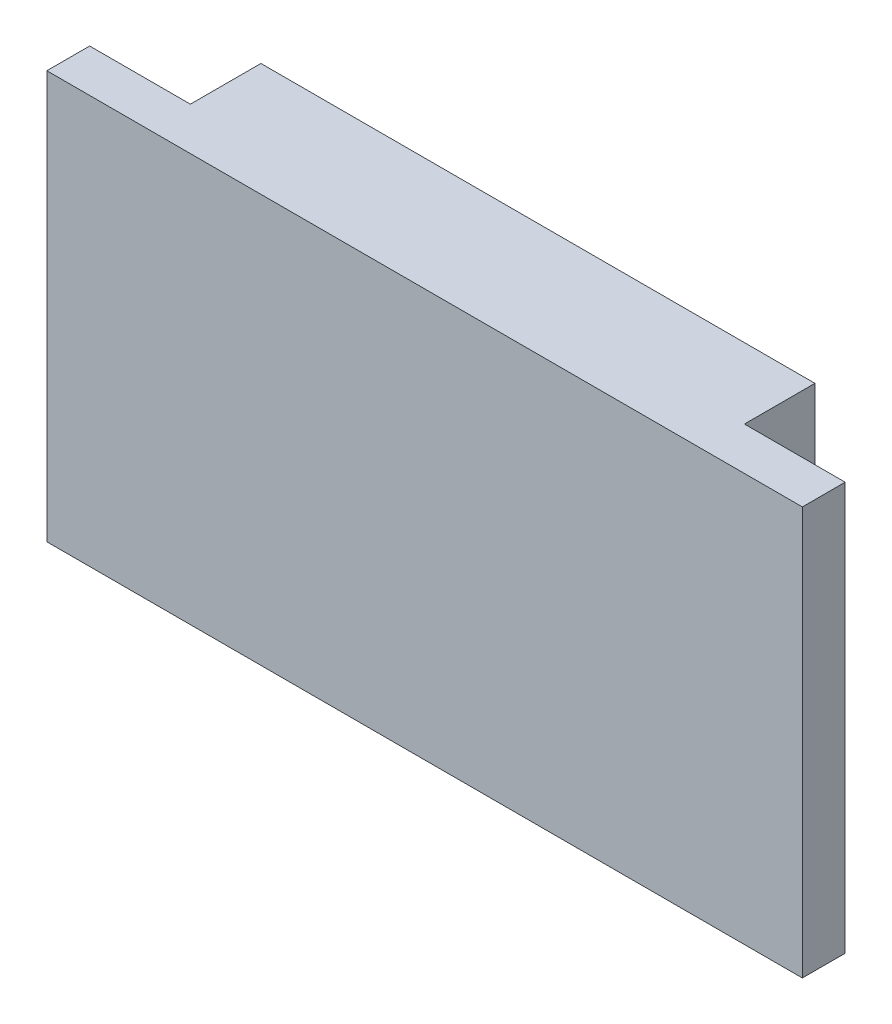
SolidWorks part; units mm, degrees
ref_plane "前视基准面" through (0, 0, 0) normal (0, 0, 1) x (1, 0, 0)
ref_plane "上视基准面" through (0, 0, 0) normal (0, 1, 0) x (1, 0, 0)
ref_plane "右视基准面" through (0, 0, 0) normal (1, 0, 0) x (0, 0, -1)
other "Configuration Table"
sketch "草图1" plane through (0, 0, 0) normal (0, 0, 1) x (1, 0, 0)
  line L6 (-15, -8.1) -> (15, -8.1)
  line L11 (-15, -8.1) -> (-15, 8.1)
  line L12 (-15, 8.1) -> (15, 8.1)
  line L13 (15, -8.1) -> (15, 8.1)
  line L14 (-15, -8.1) -> (15, 8.1) construction
  line L15 (-15, 8.1) -> (15, -8.1) construction
  point P0 (0, 0)
  dimension "D1" = 16.2
  dimension "D2" = 30
extrude "凸台-拉伸1" add sketch "草图1" along normal blind 4.5
sketch "草图2" plane through (0, 0, 0) normal (0, 0, -1) x (-1, 0, 0)
  line L0 (15, 8.1) -> (-15, 8.1) construction
  line L1 (-15, 8.1) -> (-11, 8.1)
  line L2 (-15, 8.1) -> (-15, -8.1)
  line L3 (-15, -8.1) -> (-11, -8.1)
  line L4 (-11, 8.1) -> (-11, -8.1)
  line L5 (15, -8.1) -> (-15, -8.1) construction
  line L6 (15, -8.1) -> (15, 8.1) construction
  line L7 (15, -8.1) -> (11, -8.1)
  line L8 (15, -8.1) -> (15, 8.1)
  line L9 (15, 8.1) -> (11, 8.1)
  line L10 (11, -8.1) -> (11, 8.1)
  line L11 (-15, -8.1) -> (-15, 8.1) construction
  point P14 (-13.4974, 8.1)
  dimension "D1" = 4
extrude "切除-拉伸1" cut sketch "草图2" against normal offset from surface (2.8 mm away) 1.7 up to face at (0, 0, 4.5)
